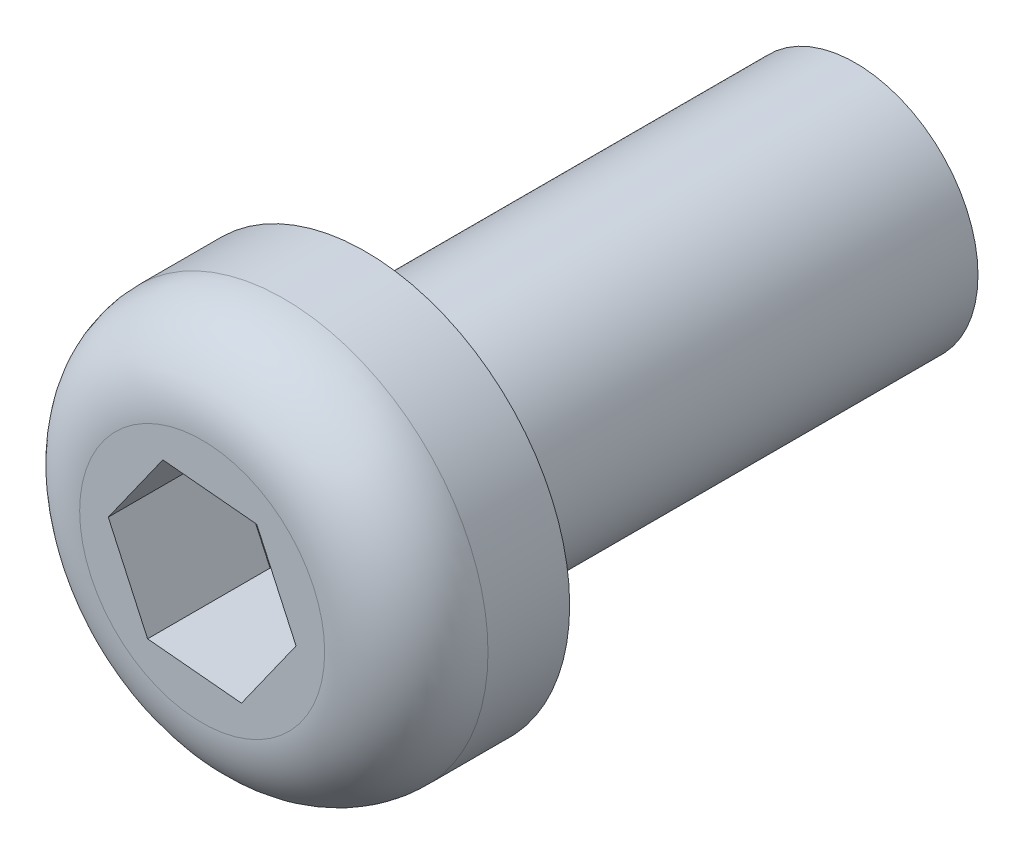
SolidWorks part; units mm, degrees
ref_plane "前视基准面" through (0, 0, 0) normal (0, 0, 1) x (1, 0, 0)
ref_plane "上视基准面" through (0, 0, 0) normal (0, 1, 0) x (1, 0, 0)
ref_plane "右视基准面" through (0, 0, 0) normal (1, 0, 0) x (0, 0, -1)
sketch "草图1" plane through (0, 0, 0) normal (0, 0, 1) x (1, 0, 0)
  circle A0 centre (0, 0) radius 1.5
  dimension "D1" = 3
extrude "凸台-拉伸1" add sketch "草图1" along normal blind 6
sketch "草图2" plane through (0, 0, 6) normal (0, 0, 1) x (1, 0, 0)
  circle A0 centre (0, 0) radius 2.5
  dimension "D1" = 5
extrude "凸台-拉伸2" add sketch "草图2" along normal blind 2
sketch "草图3" plane through (0, 0, 8) normal (0, 0, 1) x (1, 0, 0)
  line L1 (1.1496, -0.108) -> (0.6683, 0.9416)
  line L2 (0.6683, 0.9416) -> (-0.4813, 1.0496)
  line L3 (-0.4813, 1.0496) -> (-1.1496, 0.108)
  line L4 (-1.1496, 0.108) -> (-0.6683, -0.9416)
  line L5 (-0.6683, -0.9416) -> (0.4813, -1.0496)
  line L6 (0.4813, -1.0496) -> (1.1496, -0.108)
  circle A0 centre (0, 0) radius 1 construction
  dimension "D1" = 2
extrude "切除-拉伸1" cut sketch "草图3" against normal blind 1.5
fillet "圆角2" radius 1 1 edges at (2.5, 0, 8)
